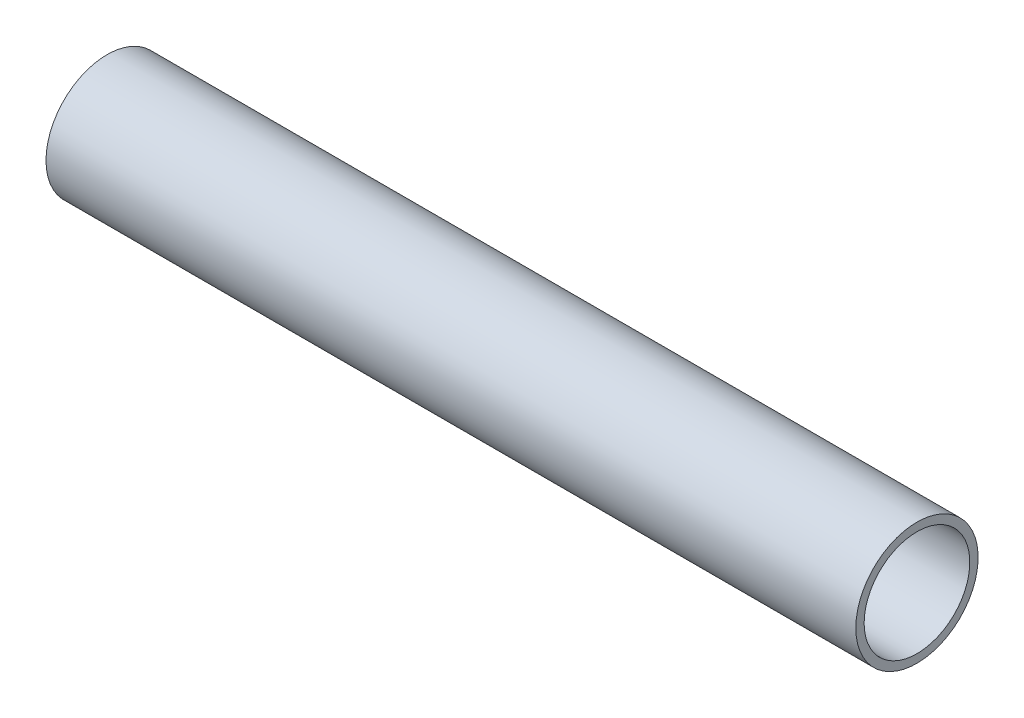
SolidWorks part; units mm, degrees
ref_plane "Front Plane" through (0, 0, 0) normal (0, 0, 1) x (1, 0, 0)
ref_plane "Top Plane" through (0, 0, 0) normal (0, 1, 0) x (1, 0, 0)
ref_plane "Right Plane" through (0, 0, 0) normal (1, 0, 0) x (0, 0, -1)
sketch "Sketch1" plane through (0, 0, 0) normal (0, 0, 1) x (1, 0, 0)
  line L0 (-5.5, 0) -> (307.5, 0) construction
  line L1 (-5.5, 0) -> (-5.5, 22.05) construction
  line L2 (5, 22.05) -> (297, 22.05)
  line L3 (5, 22.05) -> (5, 19.05)
  line L4 (5, 19.05) -> (297, 19.05)
  line L5 (297, 22.05) -> (297, 19.05)
  line L6 (307.5, 0) -> (307.5, 22.05) construction
  point P2 (302, 0)
  dimension "D1" = 5
  dimension "D2" = 5
  dimension "D" = 38.1
  dimension "G" = 3
  dimension "L" = 313
revolve "Revolve1" add sketch "Sketch1" angle 360 about L0
